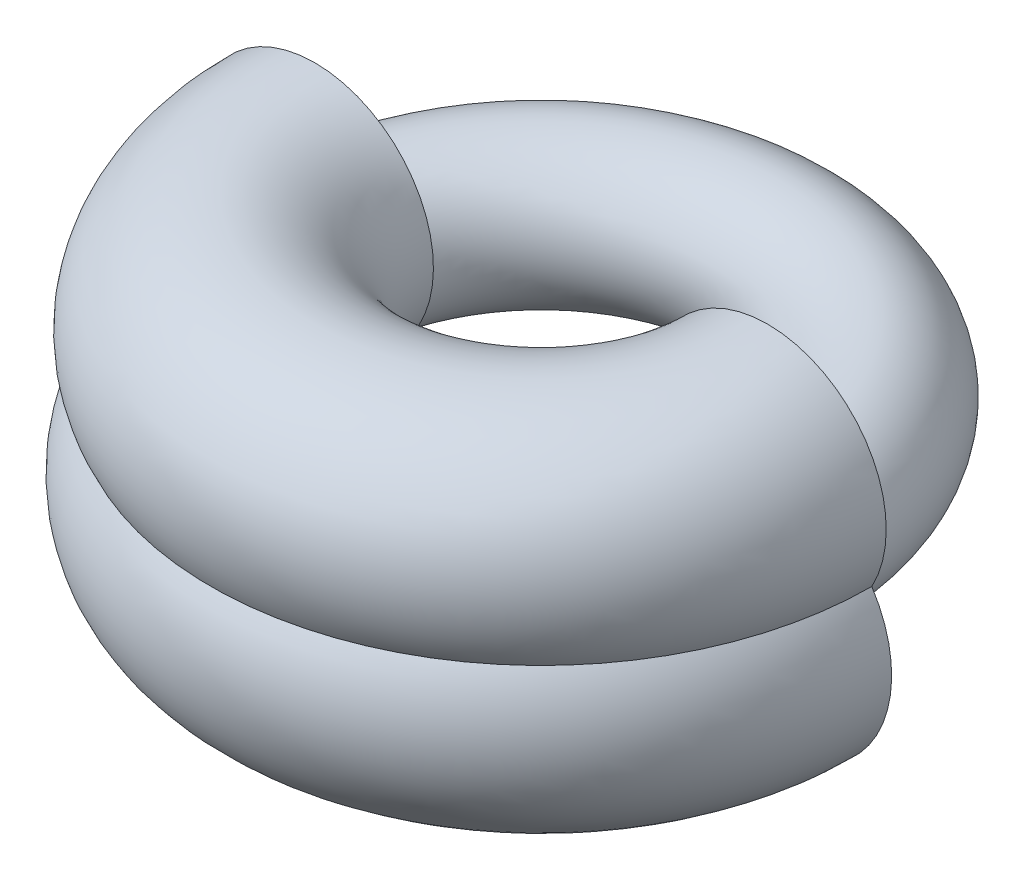
SolidWorks part; units mm, degrees
ref_plane "Front Plane" through (0, 0, 0) normal (0, 0, 1) x (1, 0, 0)
ref_plane "Top Plane" through (0, 0, 0) normal (0, 1, 0) x (1, 0, 0)
ref_plane "Right Plane" through (0, 0, 0) normal (1, 0, 0) x (0, 0, -1)
sketch "Sketch1" plane through (0, 0, 0) normal (0, 0, 1) x (1, 0, 0)
  line L0 (0, 50.7298) -> (0, -41.9072) construction
  arc A0 (12.8487, 23.0829) -> (34.7165, 23.0829) centre (23.7826, 16.0149) ccw
  arc A1 (34.7165, 23.0829) -> (12.8487, 23.0829) centre (23.7826, 29.0343) ccw
revolve "Revolve4" add sketch "Sketch1" angle 180 about L0
sketch "Sketch3" plane through (0, 0, 0) normal (0, 0, -1) x (-1, 0, 0)
  line L0 (0, 0) -> (0, 51.2296) construction
  circle A0 centre (-24.6677, 22.9927) radius 7.7917
revolve "Revolve5" add sketch "Sketch3" angle 180 about L0
